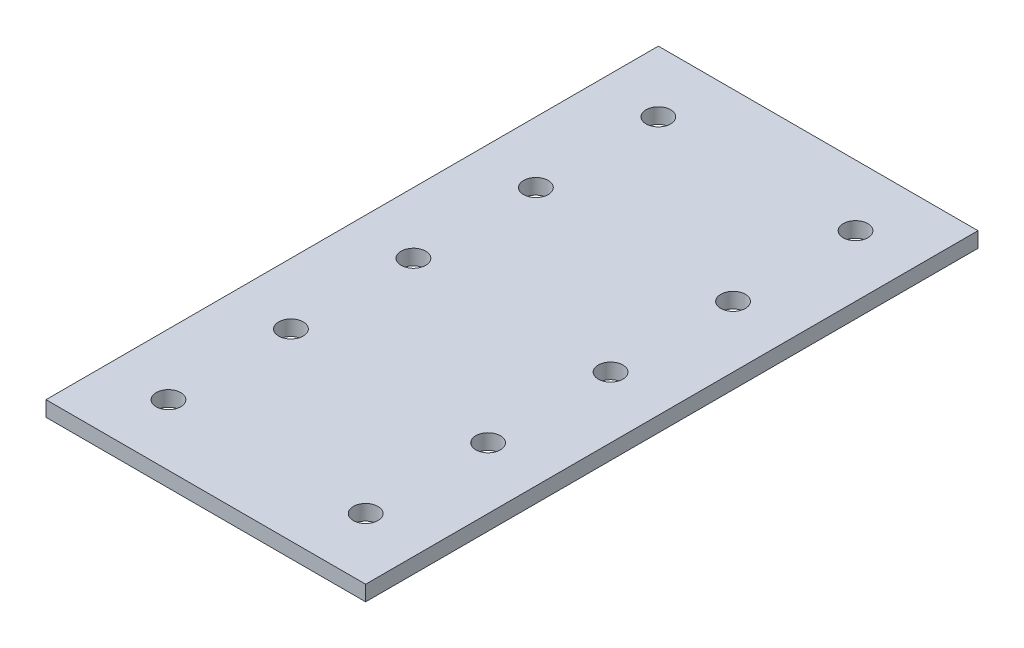
SolidWorks part; units mm, degrees
ref_plane "Front Plane" through (0, 0, 0) normal (0, 0, 1) x (1, 0, 0)
ref_plane "Top Plane" through (0, 0, 0) normal (0, 1, 0) x (1, 0, 0)
ref_plane "Right Plane" through (0, 0, 0) normal (1, 0, 0) x (0, 0, -1)
sketch "Sketch1" plane through (0, 0, 0) normal (0, 1, 0) x (1, 0, 0)
  line L1 (-33.147, -63.5) -> (33.147, -63.5)
  line L2 (-33.147, -63.5) -> (-33.147, 63.5)
  line L3 (-33.147, 63.5) -> (33.147, 63.5)
  line L4 (33.147, -63.5) -> (33.147, 63.5)
  line L5 (-33.147, -63.5) -> (33.147, 63.5) construction
  line L6 (-33.147, 63.5) -> (33.147, -63.5) construction
  point P0 (0, 0)
  dimension "D1" = 127
  dimension "D2" = 66.294
extrude "Boss-Extrude1" add sketch "Sketch1" along normal blind 3.175
sketch "Sketch2" plane through (0, 3.175, 0) normal (0, 1, 0) x (1, 0, 0)
  line L0 (-33.147, -63.5) -> (33.147, -63.5) construction
  line L1 (-33.147, 63.5) -> (-33.147, -63.5) construction
  circle A0 centre (-20.447, -50.8) radius 2.5527
  dimension "D1" = 5.1054
  dimension "D2" = 12.7
  dimension "D3" = 12.7
extrude "Cut-Extrude1" cut sketch "Sketch2" against normal blind 3.175
pattern_linear "LPattern1" count 2 spacing 40.894 along (1, 0, 0) count 5 spacing 25.4 along (0, 0, -1) of "Cut-Extrude1"
